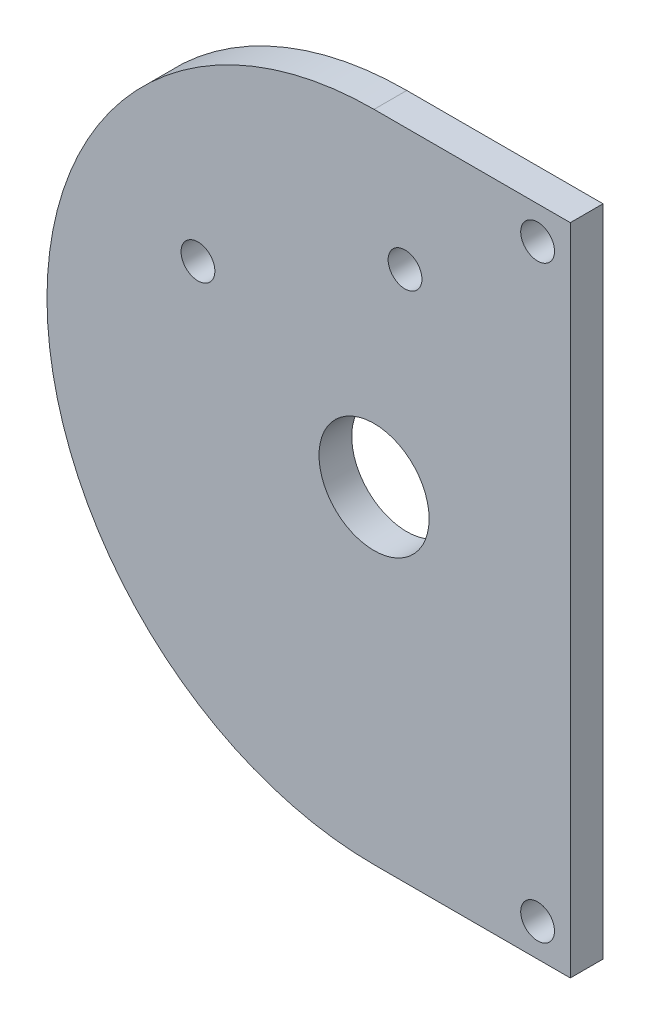
SolidWorks part; units mm, degrees
material "5052-O"
ref_plane "正面" through (0, 0, 0) normal (0, 0, 1) x (1, 0, 0)
ref_plane "平面" through (0, 0, 0) normal (0, 1, 0) x (1, 0, 0)
ref_plane "右側面" through (0, 0, 0) normal (1, 0, 0) x (0, 0, -1)
sketch "ｽｹｯﾁ1" plane through (0, 0, 0) normal (0, 0, 1) x (1, 0, 0)
  line L0 (0, -30) -> (18, -30)
  line L1 (18, -30) -> (18, 30)
  line L2 (18, 30) -> (0, 30)
  line L3 (2.8396, 18.7023) -> (-16.1521, 9.8464) construction
  line L4 (-6.6562, 14.2743) -> (0, 0) construction
  arc A0 (0, 30) -> (0, -30) centre (0, 0) ccw
  circle A1 centre (0, 0) radius 5.05
  circle A2 centre (15, 27) radius 1.55
  circle A3 centre (15, -27) radius 1.55
  circle A4 centre (-16.1521, 9.8464) radius 1.55
  circle A5 centre (2.8396, 18.7023) radius 1.55
  dimension "D1" = 30
  dimension "D3" = 10.1
  dimension "D4" = 3
  dimension "D5" = 3
  dimension "D6" = 3
  dimension "D7" = 3
  dimension "D8" = 3.1
  dimension "D2" = 18
  dimension "D9" = 25
  dimension "D10" = 20.955
  dimension "D11" = 15.75
extrude "ﾎﾞｽ - 押し出し1" add sketch "ｽｹｯﾁ1" along normal blind 3
